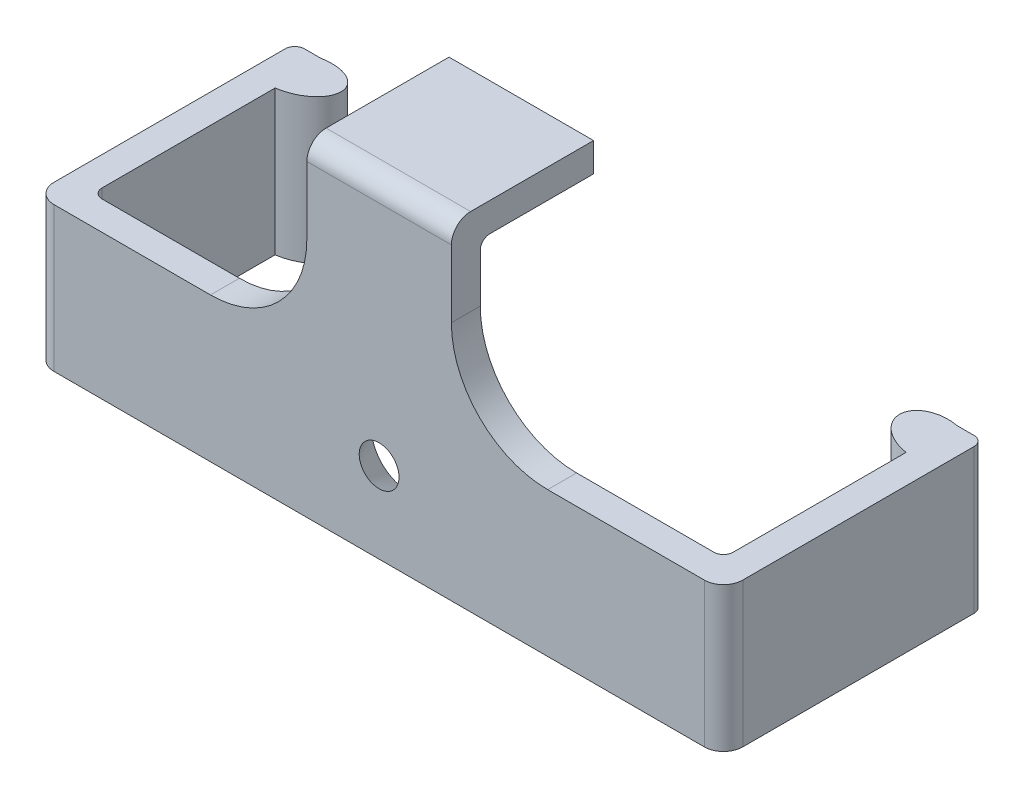
SolidWorks part; units mm, degrees
ref_plane "Спереди" through (0, 0, 0) normal (0, 0, 1) x (1, 0, 0)
ref_plane "Сверху" through (0, 0, 0) normal (0, 1, 0) x (1, 0, 0)
ref_plane "Справа" through (0, 0, 0) normal (1, 0, 0) x (0, 0, -1)
sketch "горизонт" plane through (0, 0, 0) normal (0, 1, 0) x (1, 0, 0)
  line L1 (31.75, -7) -> (-31.75, -7)
  line L2 (32.75, -6) -> (32.75, 11.955)
  line L4 (-32.75, -6) -> (-32.75, 11.955)
  line L8 (-35.75, 12) -> (-35.75, -8)
  line L9 (-32.5, -10) -> (32.5, -10)
  line L10 (35.75, 12) -> (35.75, -8)
  line L11 (-33.75, -10) -> (-32.5, -10)
  line L12 (-34.75, 17) -> (-33.75, 17)
  line L13 (-33.0198, 17) -> (-33.75, 17)
  line L14 (-35.75, 16) -> (-35.75, 12)
  line L16 (33.0198, 17) -> (33.75, 17)
  line L17 (35.75, 16) -> (35.75, 12)
  line L18 (32.5, -10) -> (33.75, -10)
  line L19 (33.75, 17) -> (34.75, 17)
  line L20 (0, 0) -> (0, 28.9286) construction
  arc A0 (31.75, -7) -> (32.75, -6) centre (31.75, -6) ccw
  arc A1 (-31.75, -7) -> (-32.75, -6) centre (-31.75, -6) cw
  arc A2 (33.75, -10) -> (35.75, -8) centre (33.75, -8) ccw
  arc A3 (-35.75, -8) -> (-33.75, -10) centre (-33.75, -8) ccw
  arc A4 (-35.75, 16) -> (-34.75, 17) centre (-34.75, 16) cw
  arc A5 (35.75, 16) -> (34.75, 17) centre (34.75, 16) ccw
  ellipse E0 centre (32.75, 14.5) end of major axis (29.0378, 15.4461) minor radius 2.5 (32.75, 11.955) -> (33.0198, 17) cw
  ellipse E2 centre (-32.75, 14.5) end of major axis (-29.0378, 15.4461) minor radius 2.5 (-32.75, 11.955) -> (-33.0198, 17) ccw
  point P0 (0, 0)
  point P5 (0, 0)
extrude "Бобышка-Вытянуть1" add sketch "горизонт" along normal blind 15
ref_plane "Плоскость4" through (0, 0, 0) normal (-1, 0, 0) x (0, 0, 1)
sketch "вертикаль" plane through (0, 0, 0) normal (-1, 0, 0) x (0, 0, 1)
  line L1 (7, 30) -> (7, 0)
  line L2 (6, 31) -> (-4.7585, 31)
  line L9 (10, 0) -> (10, 31)
  line L10 (-4.7585, 34) -> (8, 34)
  line L18 (10, 31) -> (10, 32)
  line L20 (7, 0) -> (10, 0)
  line L21 (-4.7585, 31) -> (-4.7585, 34)
  arc A0 (7, 30) -> (6, 31) centre (6, 30) ccw
  arc A2 (10, 32) -> (8, 34) centre (8, 32) ccw
  point P0 (0, -1.5)
  point P5 (0, -1.5)
  dimension "D1" = 1
  dimension "D2" = 2
extrude "Бобышка-Вытянуть3" add sketch "вертикаль" along normal blind 7.5 and the other way blind 7.5
sketch "Эскиз3" plane through (0, 0, 7) normal (0, 0, -1) x (-1, 0, 0)
  circle A0 centre (0, 8.3971) radius 3.8
extrude "Вырез-Вытянуть1" cut sketch "Эскиз3" against normal through all draft 30
fillet "Скругление2" radius 10 2 edges at (7.5, 15, 8.5) (-7.5, 15, 8.5)
